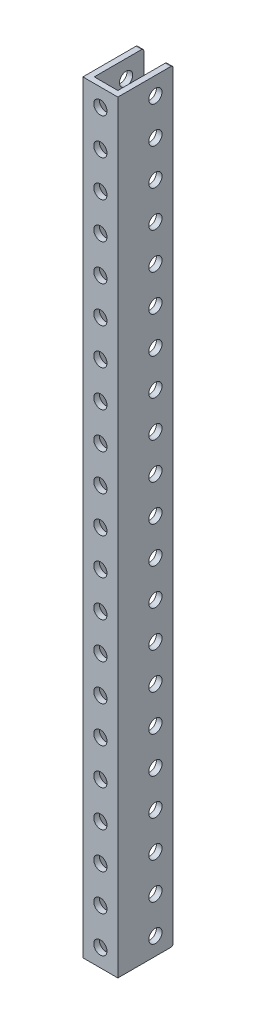
SolidWorks part; units mm, degrees
ref_plane "Front Plane" through (0, 0, 0) normal (0, 0, 1) x (1, 0, 0)
ref_plane "Top Plane" through (0, 0, 0) normal (0, 1, 0) x (1, 0, 0)
ref_plane "Right Plane" through (0, 0, 0) normal (1, 0, 0) x (0, 0, -1)
ref_plane "Plane1" through (4.699, 0, 0) normal (1, 0, 0) x (0, 0, -1)
sketch "Sketch1" plane through (4.699, 0, 0) normal (1, 0, 0) x (0, 0, -1)
  line L0 (-1.524, 0) -> (13.335, 0)
  line L1 (13.335, 0) -> (13.335, 205.105)
  line L2 (13.335, 205.105) -> (-1.524, 205.105)
  line L3 (-1.524, 205.105) -> (-1.524, 0)
extrude "Boss-Extrude1" add sketch "Sketch1" against normal blind 9.398
sketch "Sketch2" plane through (0, 0, 0) normal (0, -1, 0) x (1, 0, 0)
  line L0 (-3.175, -13.335) -> (3.175, -13.335)
  line L1 (3.175, -13.335) -> (3.175, 0)
  line L2 (3.175, 0) -> (-3.175, 0)
  line L3 (-3.175, 0) -> (-3.175, -13.335)
extrude "Cut-Extrude1" cut sketch "Sketch2" against normal through all
hole_wizard "#5 Clearance Hole1" positions "Sketch4" profile "Sketch3" hole size "#5" standard "ANSI Inch"
sketch "Sketch4" plane through (-3.175, 0, 0) normal (1, 0, 0) x (0, 0, -1)
  point P0 (8.5725, 190.5635)
  point P1 (8.5725, 200.3425)
  point P2 (8.5725, 180.7845)
  point P3 (8.5725, 171.0055)
  point P4 (8.5725, 161.2265)
  point P5 (8.5725, 151.4475)
  point P6 (8.5725, 141.6685)
  point P7 (8.5725, 131.8895)
  point P8 (8.5725, 122.1105)
  point P9 (8.5725, 112.3315)
  point P10 (8.5725, 102.5525)
  point P11 (8.5725, 92.7735)
  point P12 (8.5725, 82.9945)
  point P13 (8.5725, 73.2155)
  point P14 (8.5725, 63.4365)
  point P15 (8.5725, 53.6575)
  point P16 (8.5725, 43.8785)
  point P17 (8.5725, 34.0995)
  point P18 (8.5725, 24.3205)
  point P19 (8.5725, 14.5415)
  point P20 (8.5725, 4.7625)
sketch "Sketch3" plane through (-3.175, 190.5635, -8.5725) normal (0, 1, 0) x (0, 0, -1)
  line L0 (0, 0) -> (0, 1.524)
  line L1 (0, 1.524) -> (1.778, 1.524)
  line L2 (1.778, 1.524) -> (1.778, 0)
  line L5 (1.778, 0) -> (0, 0)
  line L11 (0, -6.35) -> (0, 107.95) construction
  dimension "Thru Hole Dia." = 3.556
  dimension "Thru Hole Depth" = 1.524
hole_wizard "#5 Clearance Hole2" positions "Sketch6" profile "Sketch5" hole size "#5" standard "ANSI Inch"
sketch "Sketch6" plane through (0, 0, 1.524) normal (0, 0, 1) x (1, 0, 0)
  point P0 (0, 190.5635)
  point P1 (0, 200.3425)
  point P2 (0, 180.7845)
  point P3 (0, 171.0055)
  point P4 (0, 161.2265)
  point P5 (0, 151.4475)
  point P6 (0, 141.6685)
  point P7 (0, 131.8895)
  point P8 (0, 122.1105)
  point P9 (0, 112.3315)
  point P10 (0, 102.5525)
  point P11 (0, 92.7735)
  point P12 (0, 82.9945)
  point P13 (0, 73.2155)
  point P14 (0, 63.4365)
  point P15 (0, 53.6575)
  point P16 (0, 43.8785)
  point P17 (0, 34.0995)
  point P18 (0, 24.3205)
  point P19 (0, 14.5415)
  point P20 (0, 4.7625)
sketch "Sketch5" plane through (0, 190.5635, 1.524) normal (1, 0, 0) x (0, -1, 0)
  line L0 (0, 0) -> (0, 14.859)
  line L1 (0, 14.859) -> (1.778, 14.859)
  line L2 (1.778, 14.859) -> (1.778, 0)
  line L5 (1.778, 0) -> (0, 0)
  line L11 (0, -6.35) -> (0, 107.95) construction
  dimension "Thru Hole Dia." = 3.556
  dimension "Thru Hole Depth" = 14.859
hole_wizard "#5 Clearance Hole3" positions "Sketch8" profile "Sketch7" hole size "#5" standard "ANSI Inch"
sketch "Sketch8" plane through (4.699, 0, 0) normal (1, 0, 0) x (0, 0, -1)
  point P0 (8.5725, 190.5635)
  point P1 (8.5725, 200.3425)
  point P2 (8.5725, 180.7845)
  point P3 (8.5725, 171.0055)
  point P4 (8.5725, 161.2265)
  point P5 (8.5725, 151.4475)
  point P6 (8.5725, 141.6685)
  point P7 (8.5725, 131.8895)
  point P8 (8.5725, 122.1105)
  point P9 (8.5725, 112.3315)
  point P10 (8.5725, 102.5525)
  point P11 (8.5725, 92.7735)
  point P12 (8.5725, 82.9945)
  point P13 (8.5725, 73.2155)
  point P14 (8.5725, 63.4365)
  point P15 (8.5725, 53.6575)
  point P16 (8.5725, 43.8785)
  point P17 (8.5725, 34.0995)
  point P18 (8.5725, 24.3205)
  point P19 (8.5725, 14.5415)
  point P20 (8.5725, 4.7625)
sketch "Sketch7" plane through (4.699, 190.5635, -8.5725) normal (0, 1, 0) x (0, 0, -1)
  line L0 (0, 0) -> (0, 9.398)
  line L1 (0, 9.398) -> (1.778, 9.398)
  line L2 (1.778, 9.398) -> (1.778, 0)
  line L5 (1.778, 0) -> (0, 0)
  line L11 (0, -6.35) -> (0, 107.95) construction
  dimension "Thru Hole Dia." = 3.556
  dimension "Thru Hole Depth" = 9.398
fillet "Fillet1" radius 0.635 4 edges at (-3.937, 0, -13.335) (-3.937, 205.105, -13.335) (3.937, 205.105, -13.335) (3.937, 0, -13.335)
